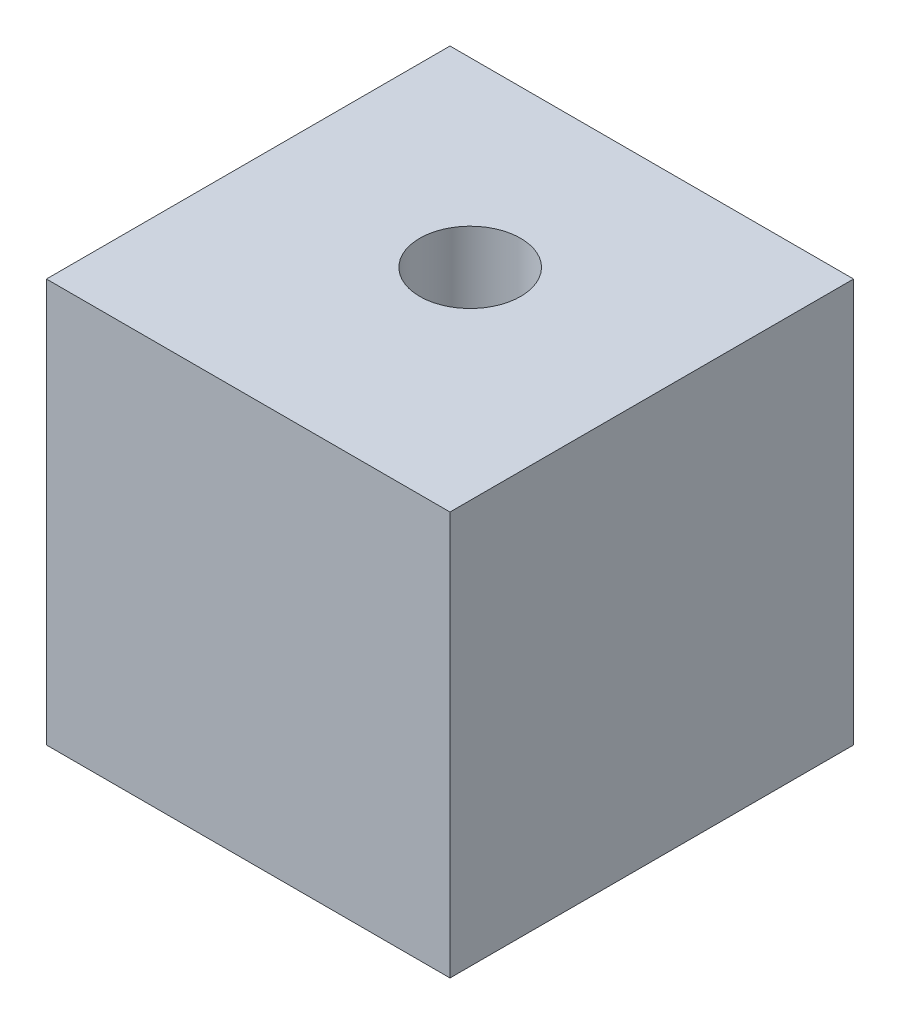
SolidWorks part; units mm, degrees
ref_plane "前视基准面" through (0, 0, 0) normal (0, 0, 1) x (1, 0, 0)
ref_plane "上视基准面" through (0, 0, 0) normal (0, 1, 0) x (1, 0, 0)
ref_plane "右视基准面" through (0, 0, 0) normal (1, 0, 0) x (0, 0, -1)
sketch "草图1" plane through (0, 0, 0) normal (0, 1, 0) x (1, 0, 0)
  line L1 (0, 0) -> (10, 0)
  line L2 (0, 0) -> (0, 10)
  line L3 (0, 10) -> (10, 10)
  line L4 (10, 0) -> (10, 10)
  dimension "D1" = 10
  dimension "D2" = 10
extrude "凸台-拉伸1" add sketch "草图1" along normal blind 10
sketch "草图3" plane through (0, 10, 0) normal (0, 1, 0) x (1, 0, 0)
  line L0 (0, 10) -> (0, 0) construction
  line L1 (10, 10) -> (0, 10) construction
  circle A0 centre (5, 5.5) radius 1.25
  dimension "D1" = 2.5
  dimension "D2" = 5
  dimension "D3" = 4.5
extrude "切除-拉伸1" cut sketch "草图3" against normal blind 10
cosmetic thread "装饰螺纹线1" parameters "D2"=3
